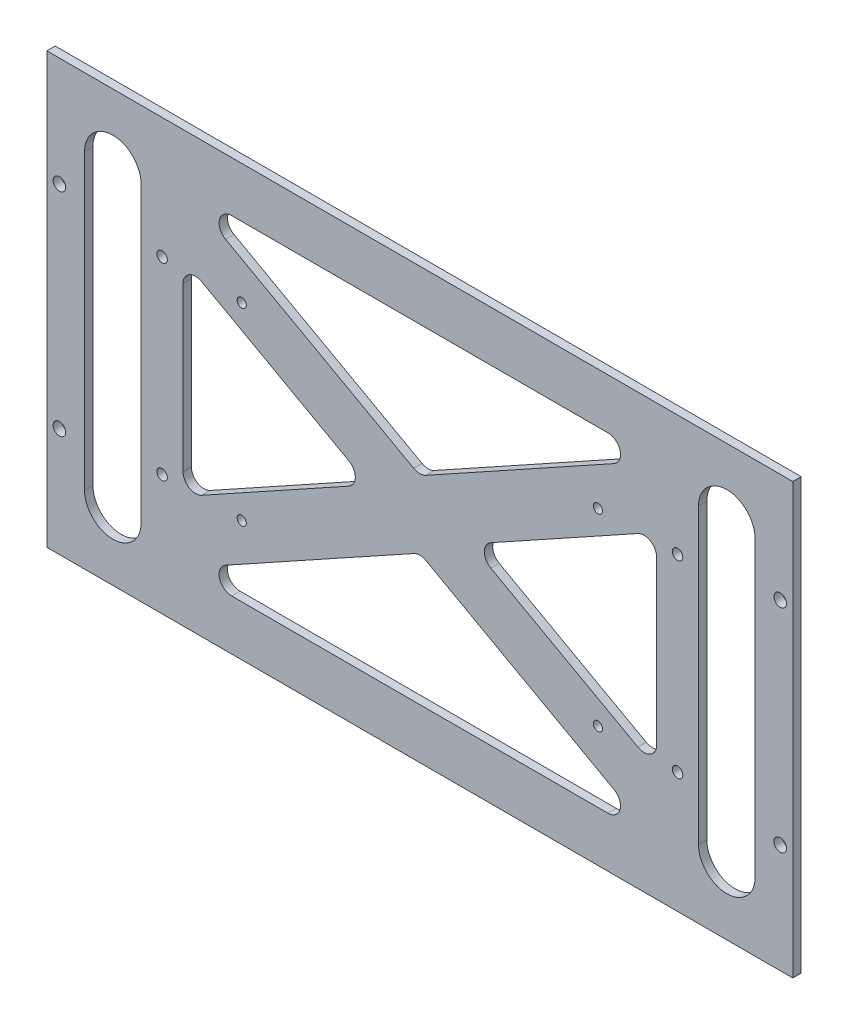
SolidWorks part; units mm, degrees
material "Thornel Mat VMA"
ref_plane "前视基准面" through (0, 0, 0) normal (0, 0, 1) x (1, 0, 0)
ref_plane "上视基准面" through (0, 0, 0) normal (0, 1, 0) x (1, 0, 0)
ref_plane "右视基准面" through (0, 0, 0) normal (1, 0, 0) x (0, 0, -1)
sketch "草图1" plane through (0, 0, 0) normal (0, 0, 1) x (1, 0, 0)
  line L0 (-234.6739, 0) -> (253.2728, 0) construction
  line L5 (0, 139.765) -> (0, -176.9627) construction
  line L7 (-89, 51.3) -> (89, 51.3)
  line L8 (-89, 51.3) -> (-89, -51.3)
  line L9 (-89, -51.3) -> (89, -51.3)
  line L10 (89, 51.3) -> (89, -51.3)
  line L11 (-89, 51.3) -> (89, -51.3) construction
  line L12 (-89, -51.3) -> (89, 51.3) construction
  line L18 (-74, -34.9) -> (74, 34.9) construction
  circle A0 centre (-86, 25.3) radius 1.5
  circle A1 centre (-86, -25.3) radius 1.5
  circle A2 centre (86, 25.3) radius 1.5
  circle A3 centre (86, -25.3) radius 1.5
  point P14 (0, 0)
  point P19 (0, 0)
  dimension "D1" = 3
  dimension "D2" = 172
  dimension "D3" = 50.6
  dimension "D4" = 178
  dimension "D5" = 102.6
extrude "凸台-拉伸1" add sketch "草图1" along normal blind 2
sketch "草图3" plane through (0, 0, 2) normal (0, 0, 1) x (1, 0, 0)
  line L0 (-61.5, -22.5) -> (61.5, -22.5) construction
  line L1 (-61.5, -22.5) -> (-61.5, 22.5) construction
  line L2 (-61.5, 22.5) -> (61.5, 22.5) construction
  line L3 (61.5, -22.5) -> (61.5, 22.5) construction
  line L4 (-61.5, -22.5) -> (61.5, 22.5) construction
  line L5 (-61.5, 22.5) -> (61.5, -22.5) construction
  line L6 (0, -49.9) -> (0, 0) construction
  line L8 (42.5, 22.5) -> (-42.5, 22.5) construction
  line L9 (42.5, 22.5) -> (42.5, -22.5) construction
  line L10 (42.5, -22.5) -> (-42.5, -22.5) construction
  line L11 (-42.5, 22.5) -> (-42.5, -22.5) construction
  line L12 (42.5, 22.5) -> (-42.5, -22.5) construction
  line L13 (42.5, -22.5) -> (-42.5, 22.5) construction
  circle A0 centre (-61.5, -22.5) radius 1.25
  circle A1 centre (-61.5, 22.5) radius 1.25
  circle A2 centre (61.5, -22.5) radius 1.25
  circle A3 centre (61.5, 22.5) radius 1.25
  circle A4 centre (-42.5, -22.5) radius 1.1
  circle A5 centre (-42.5, 22.5) radius 1.1
  circle A6 centre (42.5, 22.5) radius 1.1
  circle A7 centre (42.5, -22.5) radius 1.1
  point P4 (0, 0)
  dimension "D1" = 2.5
  dimension "D5" = 2.2
  dimension "D2" = 45
  dimension "D3" = 123
  dimension "D4" = 19
extrude "切除-拉伸1" cut sketch "草图3" against normal through all
sketch "草图4" plane through (0, 0, 2) normal (0, 0, 1) x (1, 0, 0)
  line L0 (-73.25, -35) -> (-73.25, 35) construction
  line L1 (-80, -35) -> (-80, 35)
  line L2 (-66.5, -35) -> (-66.5, 35)
  line L3 (0, -51.3) -> (0, 51.3) construction
  line L9 (-80, 0) -> (-89, 0) construction
  line L10 (-89, 51.3) -> (-89, -51.3) construction
  line L11 (-89, -51.3) -> (89, -51.3) construction
  line L12 (89, 51.3) -> (-89, 51.3) construction
  line L13 (80, 0) -> (89, 0) construction
  line L14 (73.25, -35) -> (73.25, 35) construction
  line L15 (80, -35) -> (80, 35)
  line L16 (66.5, -35) -> (66.5, 35)
  line L17 (-56.5, -24.5398) -> (-56.5, 24.5398)
  line L18 (-56.5, 24.5398) -> (-12.203, 0)
  line L19 (-12.203, 0) -> (-56.5, -24.5398)
  line L20 (-56.5, 39.3) -> (0, 8)
  line L22 (56.5, 39.3) -> (-56.5, 39.3)
  line L23 (-89, 0) -> (89, 0) construction
  line L25 (-56.5, 24.5398) -> (-56.5, 39.3) construction
  line L26 (-56.5, -24.5398) -> (-56.5, -39.3) construction
  line L27 (56.5, -39.3) -> (-56.5, -39.3)
  line L28 (-56.5, -39.3) -> (0, -8)
  line L29 (56.5, -39.3) -> (0, -8)
  line L30 (56.5, 39.3) -> (0, 8)
  line L31 (12.203, 0) -> (56.5, -24.5398)
  line L32 (56.5, 24.5398) -> (12.203, 0)
  line L33 (56.5, -24.5398) -> (56.5, -39.3) construction
  line L34 (56.5, 24.5398) -> (56.5, 39.3) construction
  line L35 (56.5, -24.5398) -> (56.5, 24.5398)
  arc A0 (-80, -35) -> (-66.5, -35) centre (-73.25, -35) ccw
  arc A1 (-66.5, 35) -> (-80, 35) centre (-73.25, 35) ccw
  circle A4 centre (-61.5, 22.5) radius 1.25 construction
  circle A5 centre (-86, 25.3) radius 1.5 construction
  arc A6 (80, -35) -> (66.5, -35) centre (73.25, -35) cw
  arc A7 (66.5, 35) -> (80, 35) centre (73.25, 35) cw
  circle A8 centre (-61.5, -22.5) radius 1.25 construction
  circle A10 centre (-42.5, 22.5) radius 1.1 construction
  point P2 (-73.25, 0)
  point P28 (73.25, 0)
  point P41 (0, 0)
  point P45 (0, -39.3)
  point P46 (0, 39.3)
  dimension "D5" = 8
  dimension "D1" = 5
  dimension "D2" = 6
  dimension "D3" = 70
  dimension "D4" = 5
  dimension "D7" = 5
  dimension "D13" = 12
extrude "切除-拉伸2" cut sketch "草图4" against normal through all
fillet "圆角1" radius 3 12 edges at (56.5, 24.5398, 1) (56.5, 39.3, 1) (56.5, -39.3, 1) (56.5, -24.5398, 1) (0, -8, 1) (0, 8, 1) (-12.203, 0, 1) (12.203, 0, 1) (-56.5, 39.3, 1) (-56.5, -39.3, 1) (-56.5, 24.5398, 1) (-56.5, -24.5398, 1)
